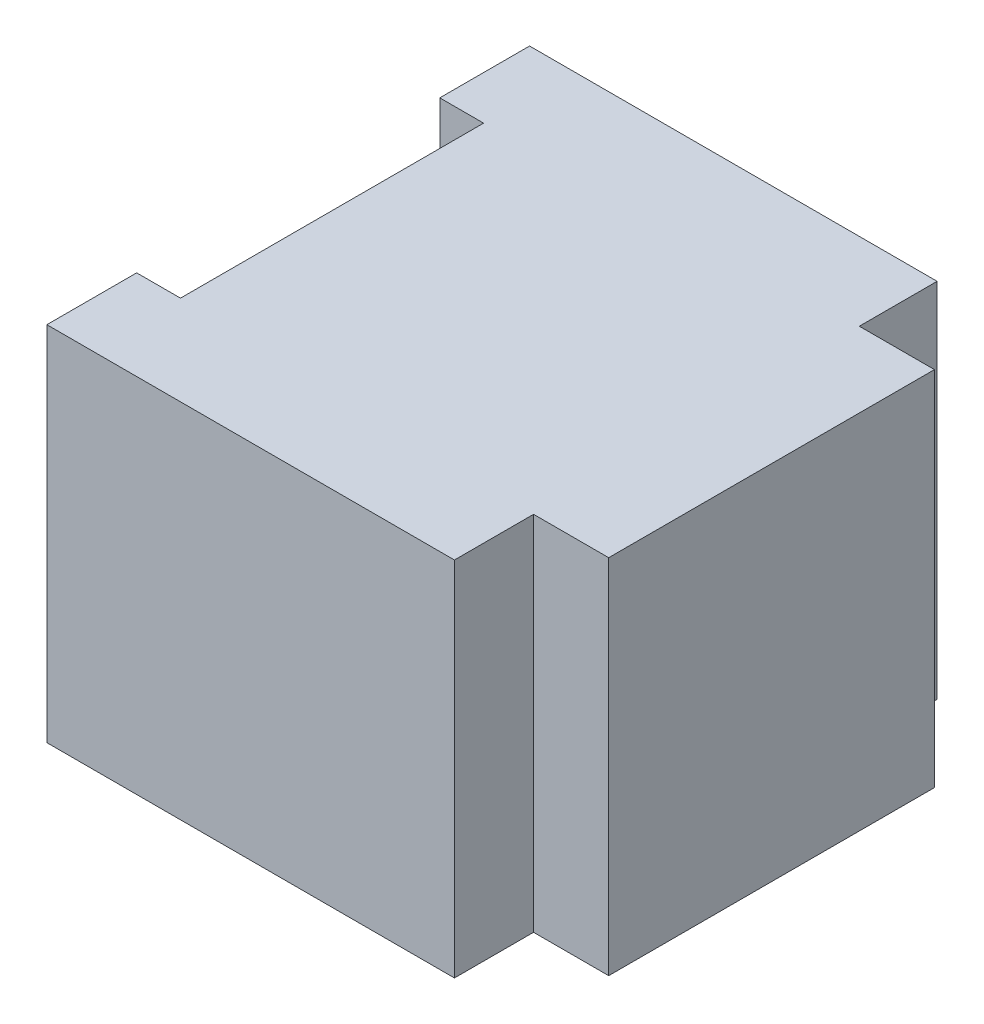
SolidWorks part; units mm, degrees
ref_plane "Front Plane" through (0, 0, 0) normal (0, 0, 1) x (1, 0, 0)
ref_plane "Top Plane" through (0, 0, 0) normal (0, 1, 0) x (1, 0, 0)
ref_plane "Right Plane" through (0, 0, 0) normal (1, 0, 0) x (0, 0, -1)
sketch "Sketch1" plane through (0, 0, 0) normal (0, 1, 0) x (1, 0, 0)
  line L1 (-40, -40) -> (40, -40)
  line L2 (-40, -40) -> (-40, 40)
  line L3 (-40, 40) -> (40, 40)
  line L4 (40, -40) -> (40, 40)
  line L5 (-40, -40) -> (40, 40) construction
  line L6 (-40, 40) -> (40, -40) construction
  point P0 (0, 0)
  dimension "D1" = 80
  dimension "D2" = 80
extrude "Boss-Extrude1" add sketch "Sketch1" along normal blind 60
sketch "Sketch2" plane through (0, 60, 0) normal (0, 1, 0) x (1, 0, 0)
  line L0 (-40, 40) -> (-40, -40) construction
  line L1 (-40, 25.1186) -> (-32.7371, 25.1186)
  line L2 (-40, 25.1186) -> (-40, -25.1186)
  line L3 (-40, -25.1186) -> (-32.7371, -25.1186)
  line L4 (-32.7371, 25.1186) -> (-32.7371, -25.1186)
extrude "Cut-Extrude1" cut sketch "Sketch2" against normal through all
sketch "Sketch3" plane through (0, 60, 0) normal (0, 1, 0) x (1, 0, 0)
  line L1 (40, 40) -> (27.5477, 40)
  line L2 (40, 40) -> (40, 27.1061)
  line L3 (40, 27.1061) -> (27.5477, 27.1061)
  line L4 (27.5477, 40) -> (27.5477, 27.1061)
  line L5 (40, -40) -> (27.5477, -40)
  line L6 (40, -40) -> (40, -26.8852)
  line L7 (40, -26.8852) -> (27.5477, -26.8852)
  line L8 (27.5477, -40) -> (27.5477, -26.8852)
extrude "Cut-Extrude2" cut sketch "Sketch3" against normal through all
